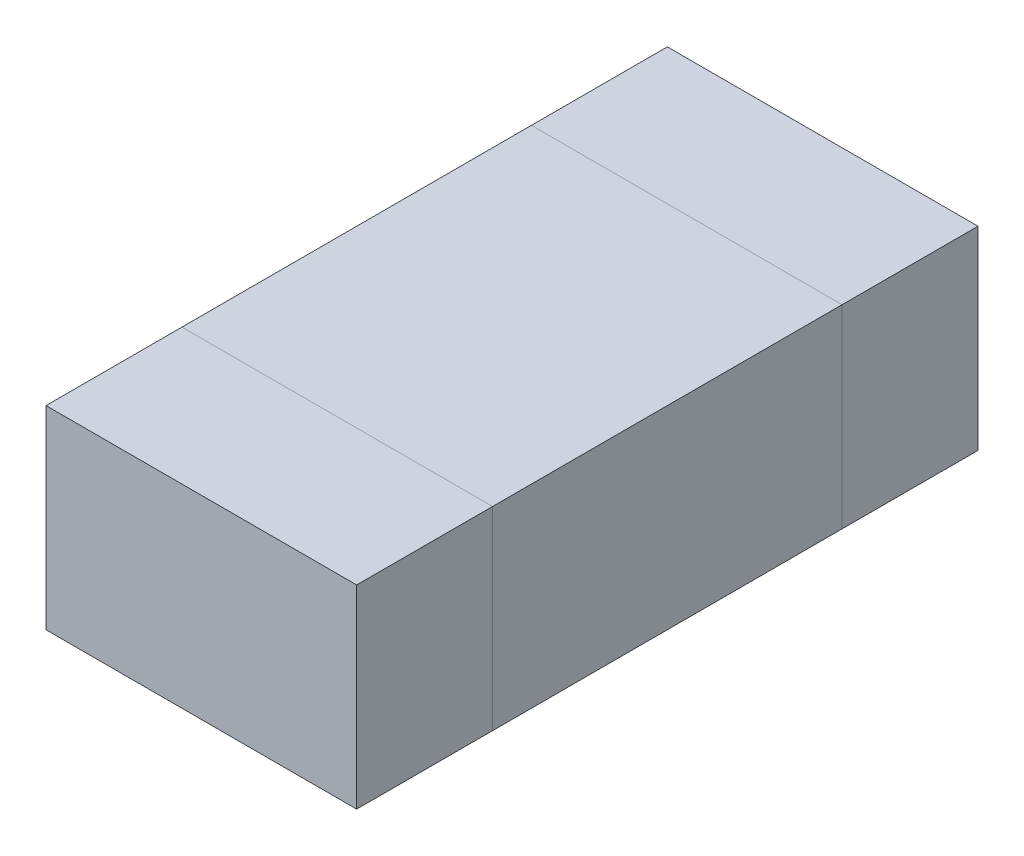
SolidWorks part; units mm, degrees
ref_plane "Front Plane" through (0, 0, 0) normal (0, 0, 1) x (1, 0, 0)
ref_plane "Top Plane" through (0, 0, 0) normal (0, 1, 0) x (1, 0, 0)
ref_plane "Right Plane" through (0, 0, 0) normal (1, 0, 0) x (0, 0, -1)
sketch "Sketch1" plane through (0, 0, 0) normal (0, 1, 0) x (1, 0, 0)
  line L1 (-0.8, 0.9) -> (0.8, 0.9)
  line L2 (-0.8, 0.9) -> (-0.8, -0.9)
  line L3 (-0.8, -0.9) -> (0.8, -0.9)
  line L4 (0.8, 0.9) -> (0.8, -0.9)
  line L5 (-0.8, 0.9) -> (0.8, -0.9) construction
  line L6 (-0.8, -0.9) -> (0.8, 0.9) construction
  point P0 (0, 0)
  dimension "D1" = 1.8
  dimension "D2" = 1.6
extrude "MB" add sketch "Sketch1" along normal blind 1
sketch "Sketch2" plane through (0, 0, 0.9) normal (0, 0, 1) x (1, 0, 0)
  line L4 (-0.8, 0) -> (0.8, 0)
  line L5 (0.8, 0) -> (0.8, 1)
  line L6 (0.8, 1) -> (-0.8, 1)
  line L7 (-0.8, 1) -> (-0.8, 0)
  line L8 (-0.8, 0) -> (0.8, 0)
  line L9 (0.8, 0) -> (0.8, 1)
  line L10 (0.8, 1) -> (-0.8, 1)
  line L11 (-0.8, 1) -> (-0.8, 0)
  dimension "D1" = 0
extrude "SB L" add sketch "Sketch2" along normal blind 0.7 separate body
sketch "Sketch3" plane through (0, 0, -0.9) normal (0, 0, -1) x (-1, 0, 0)
  line L4 (-0.8, 0) -> (0.8, 0)
  line L5 (0.8, 0) -> (0.8, 1)
  line L6 (0.8, 1) -> (-0.8, 1)
  line L7 (-0.8, 1) -> (-0.8, 0)
  line L8 (-0.8, 0) -> (0.8, 0)
  line L9 (0.8, 0) -> (0.8, 1)
  line L10 (0.8, 1) -> (-0.8, 1)
  line L11 (-0.8, 1) -> (-0.8, 0)
  dimension "D1" = 0
extrude "SB R" add sketch "Sketch3" along normal blind 0.7 separate body
